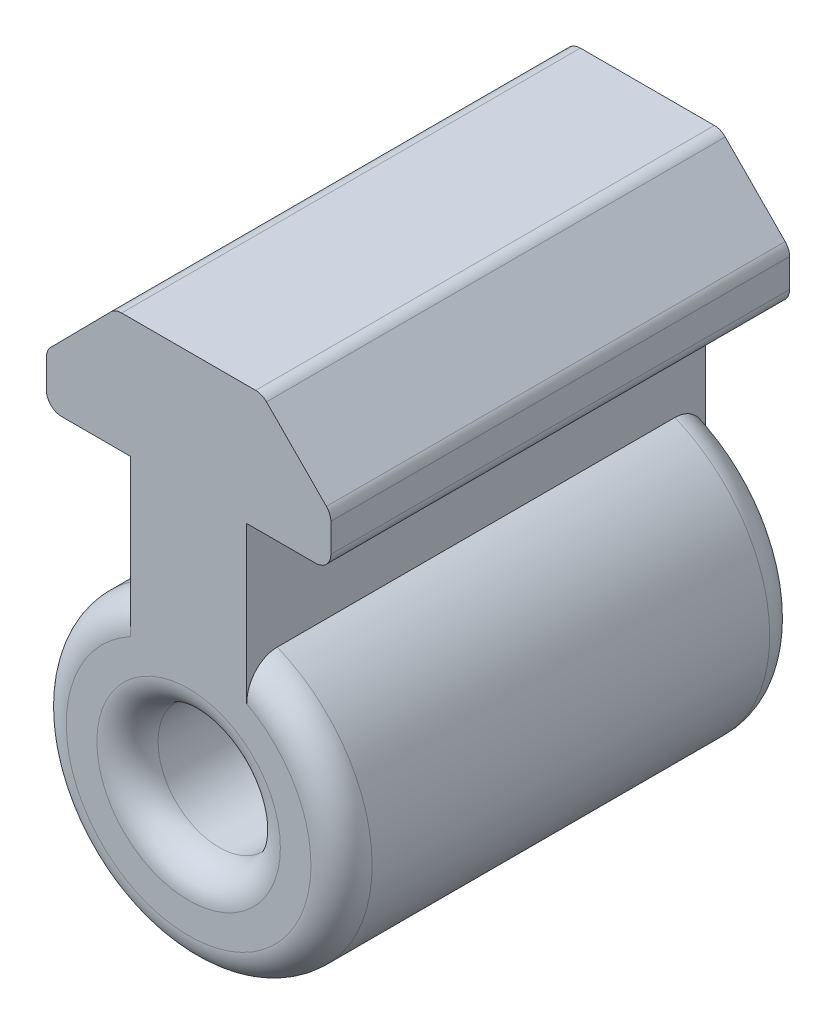
SolidWorks part; units mm, degrees
ref_plane "Front Plane" through (0, 0, 0) normal (0, 0, 1) x (1, 0, 0)
ref_plane "Top Plane" through (0, 0, 0) normal (0, 1, 0) x (1, 0, 0)
ref_plane "Right Plane" through (0, 0, 0) normal (1, 0, 0) x (0, 0, -1)
sketch "Sketch1" plane through (0, 0, 0) normal (0, 0, 1) x (1, 0, 0)
  line L0 (0, 0) -> (0, 44.9793) construction
  line L5 (3.8, 0) -> (-3.8, 0)
  line L6 (-3.8, 0) -> (-3.8, 8)
  line L7 (-3.8, 8) -> (-9.3, 8)
  line L8 (-9.3, 8) -> (-9.3, 11.28)
  line L9 (-9.3, 11.28) -> (-4.8, 15.8308)
  line L10 (-4.8, 15.8308) -> (4.8, 15.8308)
  line L11 (0, 15.8308) -> (0, 0) construction
  line L12 (9.3, 11.28) -> (4.8, 15.8308)
  line L13 (9.3, 8) -> (9.3, 11.28)
  line L14 (3.8, 8) -> (9.3, 8)
  line L15 (3.8, 0) -> (3.8, 8)
  dimension "D1" = 3.8
  dimension "D2" = 8
  dimension "D3" = 5.5
  dimension "D4" = 3.28
  dimension "D5" = 6.4
  dimension "D6" = 4.8
extrude "Boss-Extrude1" add sketch "Sketch1" along normal blind 30
fillet "Fillet1" radius 1 6 edges at (9.3, 8, 15) (-9.3, 8, 15) (-9.3, 11.28, 15) (9.3, 11.28, 15) (-4.8, 15.8308, 15) (4.8, 15.8308, 15)
sketch "Sketch3" plane through (0, 0, 0) normal (0, 0, -1) x (-1, 0, 0)
  line L0 (0, 0) -> (0, -50000) construction
  circle A0 centre (0, -9.2499) radius 4
  circle A1 centre (0, -9.2499) radius 10
  dimension "D1" = 20
  dimension "D2" = 8
extrude "Boss-Extrude2" add sketch "Sketch3" against normal up to surface (30 mm away) up to face at (0, 9.8373, 30)
fillet "Fillet2" radius 2 4 edges at (0, -19.2499, 0) (0, -19.2499, 30) (-4, -9.2499, 30) (-4, -9.2499, 0)
